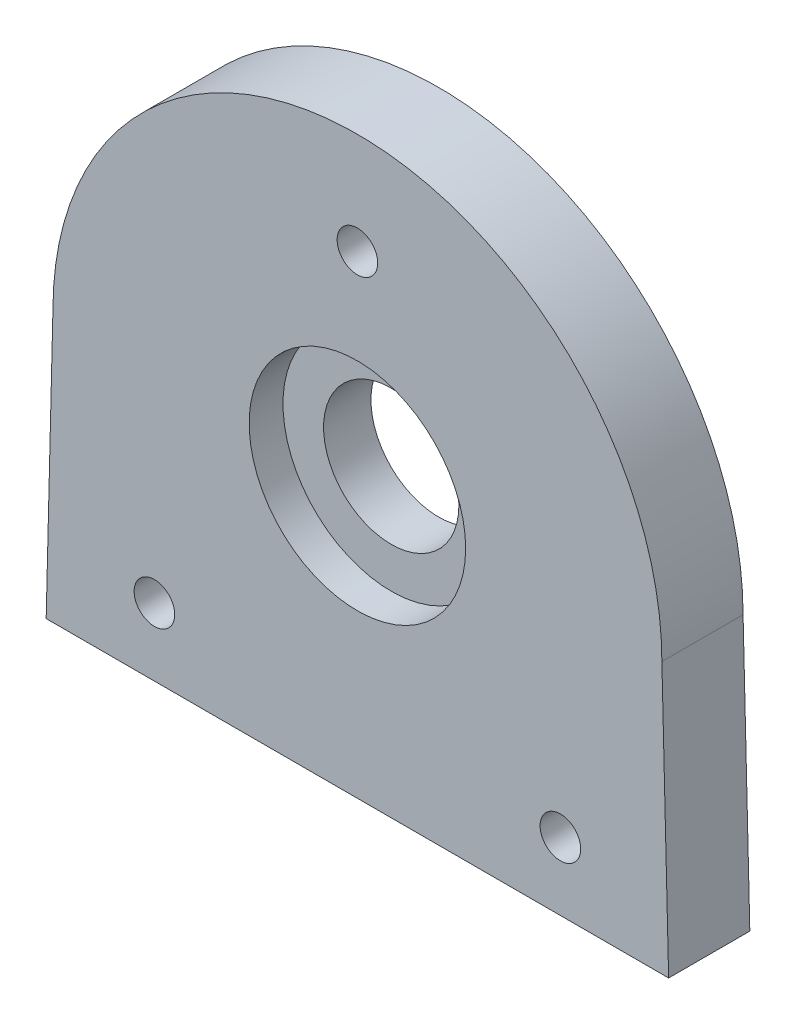
SolidWorks part; units mm, degrees
material "Acrylic (Medium-high impact)"
ref_plane "Front Plane" through (0, 0, 0) normal (0, 0, 1) x (1, 0, 0)
ref_plane "Top Plane" through (0, 0, 0) normal (0, 1, 0) x (1, 0, 0)
ref_plane "Right Plane" through (0, 0, 0) normal (1, 0, 0) x (0, 0, -1)
sketch "Sketch1" plane through (0, 0, 0) normal (0, 0, 1) x (1, 0, 0)
  line L0 (0, 35.9527) -> (0, -67.8) construction
  line L1 (-22.5, 0) -> (-22.9993, -20)
  line L2 (22.5, 0) -> (22.9993, -20)
  line L3 (22.9993, -20) -> (0, -20)
  line L4 (0, -20) -> (-22.9993, -20)
  arc A0 (22.5, 0) -> (-22.5, 0) centre (0, 0) ccw
  dimension "D1" = 45
  dimension "D2" = 1.43
  dimension "D3" = 20
extrude "Bearing Holder Boss-Extrude1" add sketch "Sketch1" against normal blind 6
sketch "Sketch2" plane through (0, 0, 0) normal (0, 0, 1) x (1, 0, 0)
  circle A0 centre (0, 0) radius 8
  dimension "D1" = 16
extrude "Bearing Hole Cut-Extrude1" cut sketch "Sketch2" against normal blind 2.5
sketch "Sketch3" plane through (0, 0, -2.5) normal (0, 0, 1) x (1, 0, 0)
  circle A0 centre (0, 0) radius 5
  dimension "D1" = 10
extrude "Shaft Hole Cut-Extrude2" cut sketch "Sketch3" against normal up to surface (3.5 mm away) up to face at (0, -4.375, -6)
sketch "Sketch4" plane through (0, 0, 0) normal (0, 0, 1) x (1, 0, 0)
  line L0 (15, -15) -> (0, -15) construction
  line L1 (0, -15) -> (-15, -15) construction
  line L2 (0, -15) -> (0, 0) construction
  line L3 (0, 0) -> (0, 15) construction
  circle A0 centre (0, 15) radius 1.5
  circle A1 centre (-15, -15) radius 1.5
  circle A2 centre (15, -15) radius 1.5
  dimension "D1" = 3
  dimension "D2" = 15
extrude "Mounting Holes Cut-Extrude3" cut sketch "Sketch4" against normal up to surface (6 mm away) up to face at (5, 0, -6)
